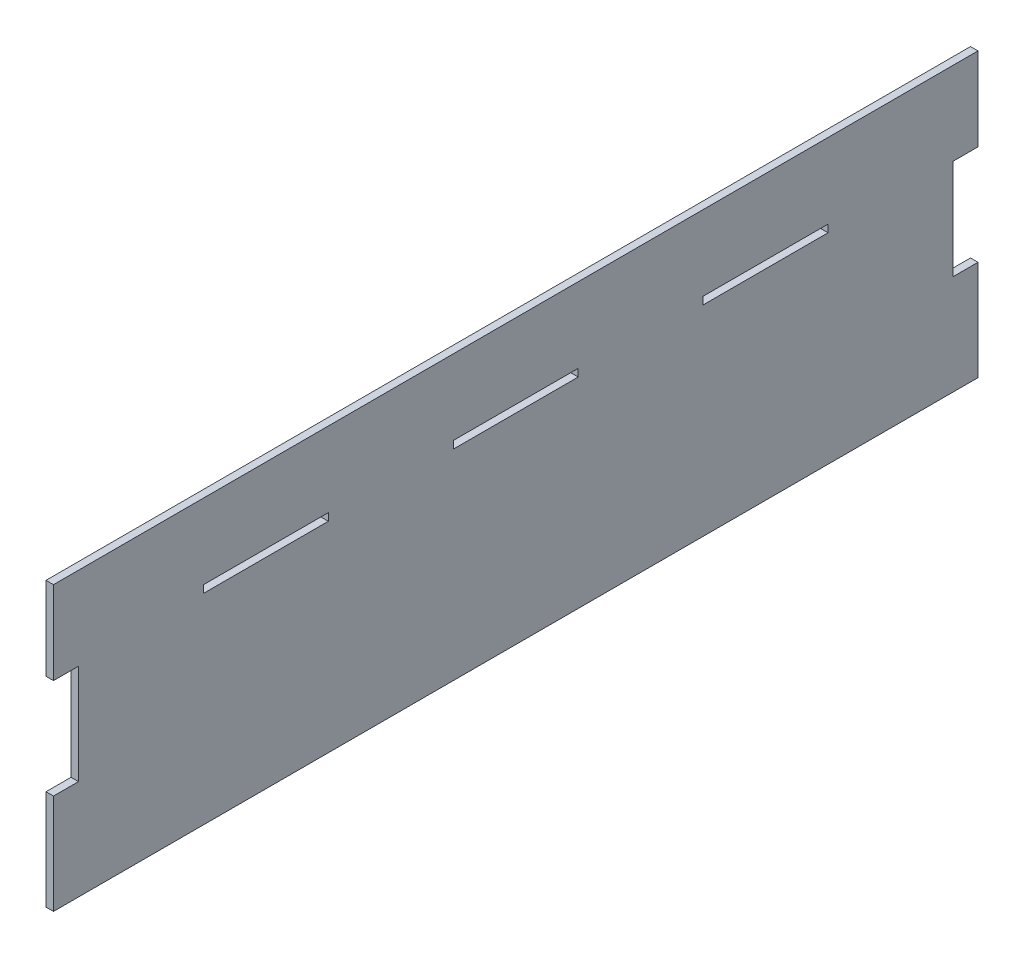
SolidWorks part; units mm, degrees
material "아크릴(내충격성)"
ref_plane "정면" through (0, 0, 0) normal (0, 0, 1) x (1, 0, 0)
ref_plane "윗면" through (0, 0, 0) normal (0, 1, 0) x (1, 0, 0)
ref_plane "우측면" through (0, 0, 0) normal (1, 0, 0) x (0, 0, -1)
sketch "스케치1" plane through (0, 0, 0) normal (1, 0, 0) x (0, 0, -1)
  line L0 (0, 111.1765) -> (0, -107.7176) construction
  line L1 (185, 90.4235) -> (-185, 90.4235)
  line L2 (-185, 90.4235) -> (-185, 57.1535)
  line L4 (-175, 90.4235) -> (-175, -29.5765) construction
  line L5 (-185, 17.1535) -> (-185, -22.8465)
  line L9 (-185, 17.1535) -> (-175, 17.1535)
  line L10 (-175, 17.1535) -> (-175, 57.1535)
  line L11 (-175, 57.1535) -> (-185, 57.1535)
  line L29 (175, 90.4235) -> (175, -29.5765) construction
  line L33 (185, 17.1535) -> (185, -22.8465)
  line L34 (185, 17.1535) -> (175, 17.1535)
  line L35 (175, 17.1535) -> (175, 57.1535)
  line L36 (175, 57.1535) -> (185, 57.1535)
  line L37 (185, 90.4235) -> (185, 57.1535)
  line L45 (-185, 57.3835) -> (185, 57.3835) construction
  line L46 (-185, -22.8465) -> (185, -22.8465)
  line L47 (-125, 57.3835) -> (-75, 57.3835)
  line L48 (-125, 57.3835) -> (-125, 60.3835)
  line L49 (-125, 60.3835) -> (-75, 60.3835)
  line L50 (-75, 57.3835) -> (-75, 60.3835)
  line L51 (-25, 57.3835) -> (25, 57.3835)
  line L52 (-25, 57.3835) -> (-25, 60.3835)
  line L53 (-25, 60.3835) -> (25, 60.3835)
  line L54 (25, 57.3835) -> (25, 60.3835)
  line L55 (75, 57.3835) -> (125, 57.3835)
  line L56 (75, 57.3835) -> (75, 60.3835)
  line L57 (75, 60.3835) -> (125, 60.3835)
  line L58 (125, 57.3835) -> (125, 60.3835)
  point P9 (0, -19.5765)
  point P10 (0, -19.5765)
  point P23 (0, -29.5765)
  point P24 (0, 90.4235)
  point P38 (0, 90.4235)
  dimension "D1" = 185
  dimension "D5" = 10
  dimension "D6" = 40
  dimension "D9" = 3
  dimension "D10" = 3
  dimension "D11" = 3
  dimension "D12" = 33.27
extrude "보스-돌출1" add sketch "스케치1" along normal blind 3
